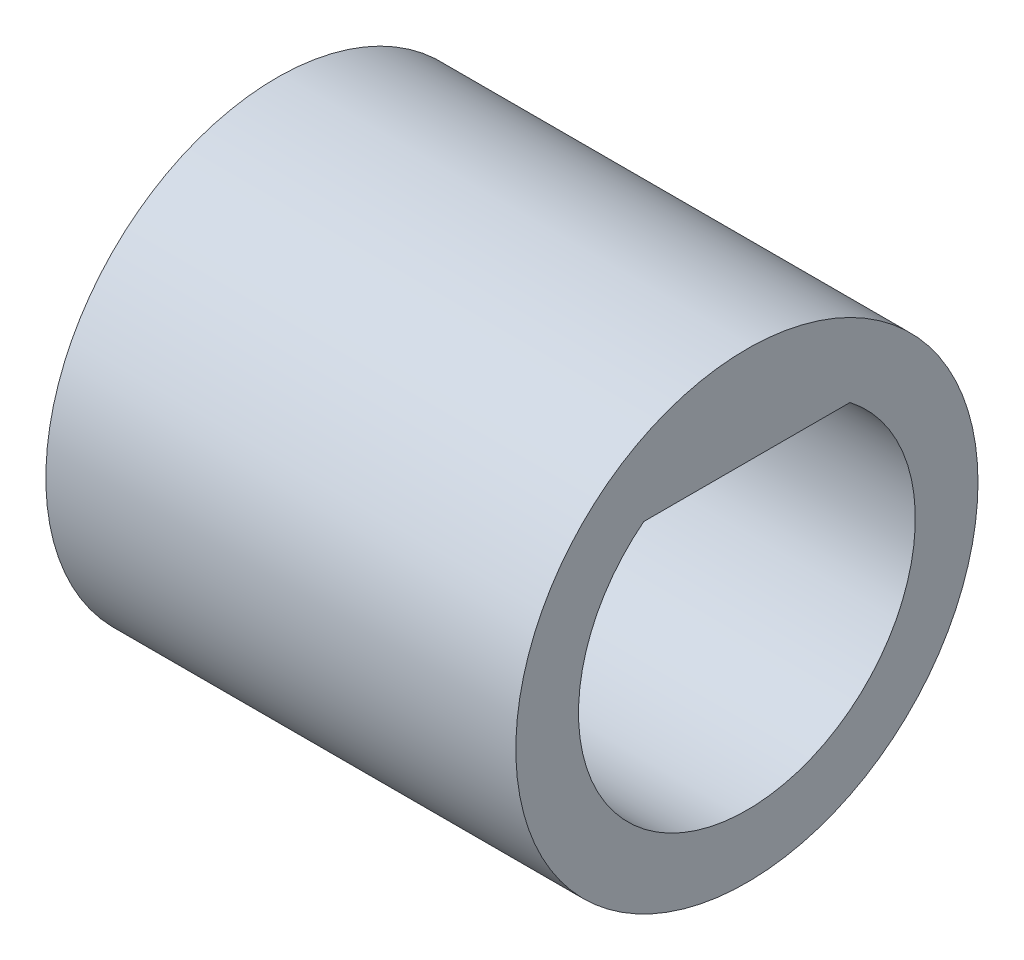
SolidWorks part; units mm, degrees
ref_plane "Front Plane" through (0, 0, 0) normal (0, 0, 1) x (1, 0, 0)
ref_plane "Top Plane" through (0, 0, 0) normal (0, 1, 0) x (1, 0, 0)
ref_plane "Right Plane" through (0, 0, 0) normal (1, 0, 0) x (0, 0, -1)
sketch "Sketch1" plane through (0, 0, 0) normal (1, 0, 0) x (0, 0, -1)
  line L0 (-1.9, 1.8473) -> (-1.9, -1.8473)
  line L1 (1.9, 1.8473) -> (1.9, -1.8473)
  arc A0 (-1.9, -1.8473) -> (1.9, -1.8473) centre (0, 0) ccw
  arc A2 (1.9, 1.8473) -> (-1.9, 1.8473) centre (0, 0) ccw
  dimension "D3" = 5.3
  dimension "D1" = 3.8
  dimension "D2" = 1.9
sketch "Sketch5" plane through (0, 0, 0) normal (1, 0, 0) x (0, 0, -1)
  line L0 (-1.3162, 1.7) -> (1.3162, 1.7) construction
  arc A0 (-1.3162, 1.7) -> (1.3162, 1.7) centre (0, 0) ccw construction
  circle A1 centre (0, 0) radius 2.95
  dimension "D1" = 4.3
  dimension "D3" = 5.9
  dimension "D2" = 1.7
extrude "Boss-Extrude2" add sketch "Sketch5" along normal blind 6 contours A1
sketch "Sketch7" plane through (6, 0, 0) normal (1, 0, 0) x (0, 0, -1)
  line L0 (-1.3162, 1.7) -> (1.3162, 1.7)
  arc A0 (-1.3162, 1.7) -> (1.3162, 1.7) centre (0, 0) ccw
  arc A1 (-1.3162, 1.7) -> (1.3162, 1.7) centre (0, 0) ccw construction
extrude "Cut-Extrude1" cut sketch "Sketch7" against normal blind 5
equation "\"D2@Sketch1\"=\"D1@Sketch1\"/2"
equation "\"D3@Sketch5\"=(2.15+0.8)*2"
